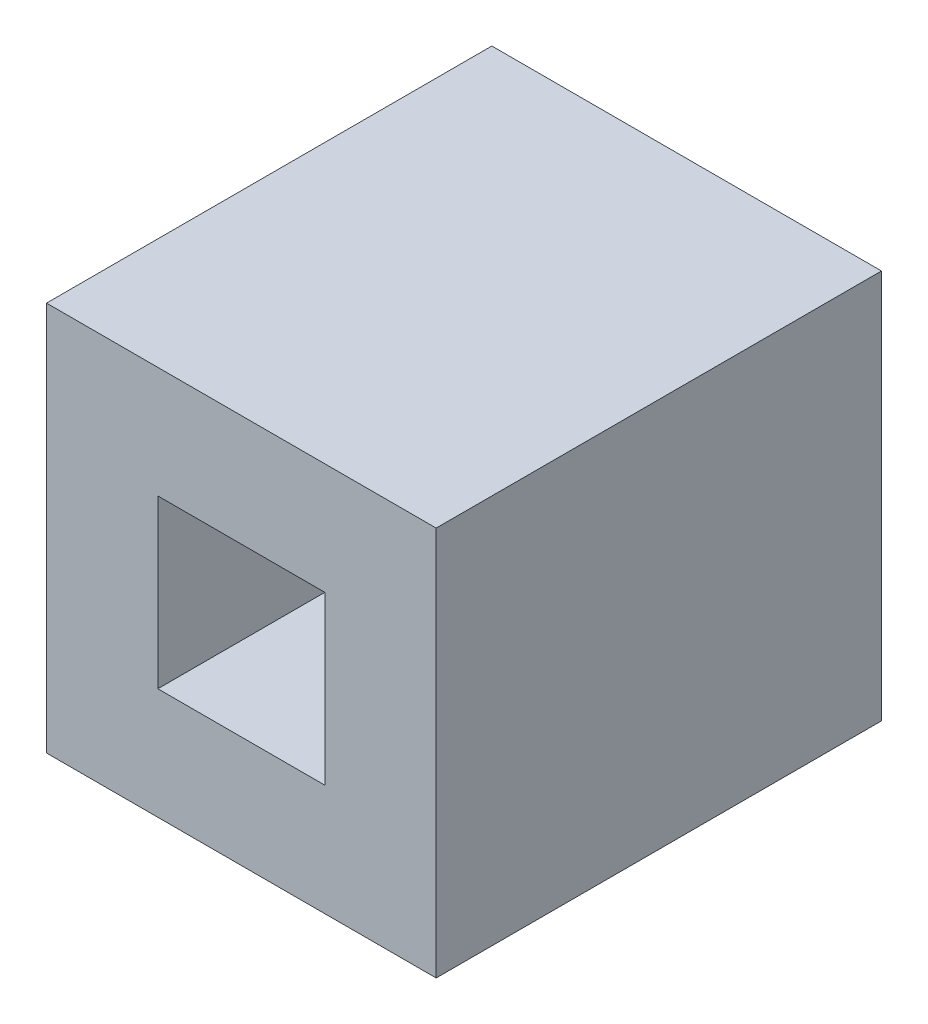
SolidWorks part; units mm, degrees
ref_plane "前视基准面" through (0, 0, 0) normal (0, 0, 1) x (1, 0, 0)
ref_plane "上视基准面" through (0, 0, 0) normal (0, 1, 0) x (1, 0, 0)
ref_plane "右视基准面" through (0, 0, 0) normal (1, 0, 0) x (0, 0, -1)
sketch "草图1" plane through (0, 0, 0) normal (0, 0, 1) x (1, 0, 0)
  line L1 (-17.5, -17.5) -> (17.5, -17.5)
  line L2 (-17.5, -17.5) -> (-17.5, 17.5)
  line L3 (-17.5, 17.5) -> (17.5, 17.5)
  line L4 (17.5, -17.5) -> (17.5, 17.5)
  line L5 (-17.5, -17.5) -> (17.5, 17.5) construction
  line L6 (-17.5, 17.5) -> (17.5, -17.5) construction
  line L7 (-7.5, -7.5) -> (7.5, -7.5)
  line L8 (-7.5, -7.5) -> (-7.5, 7.5)
  line L9 (-7.5, 7.5) -> (7.5, 7.5)
  line L10 (7.5, -7.5) -> (7.5, 7.5)
  line L11 (-7.5, -7.5) -> (7.5, 7.5) construction
  line L12 (-7.5, 7.5) -> (7.5, -7.5) construction
  point P0 (0, 0)
  point P6 (0, 0)
  dimension "D1" = 15
  dimension "D2" = 15
  dimension "D3" = 35
  dimension "D4" = 35
extrude "凸台-拉伸1" add sketch "草图1" along normal blind 40
